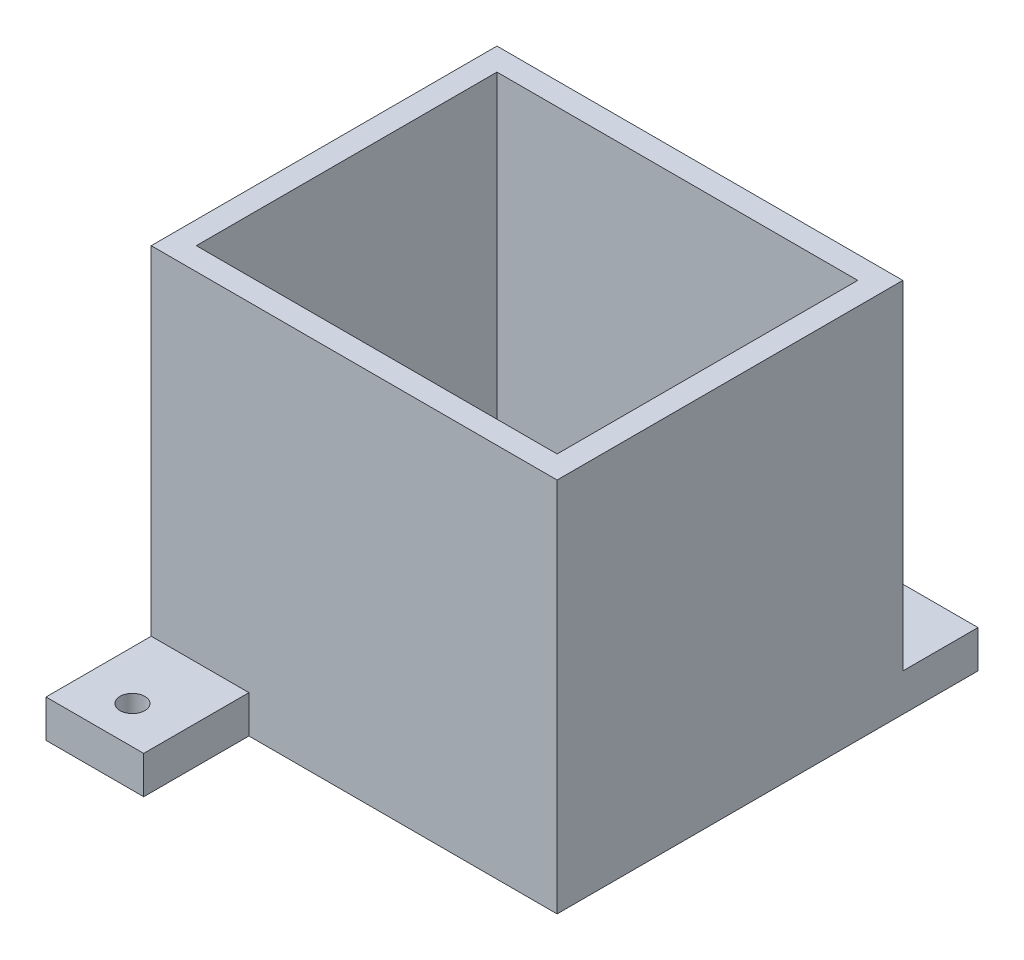
SolidWorks part; units mm, degrees
ref_plane "Front Plane" through (0, 0, 0) normal (0, 0, 1) x (1, 0, 0)
ref_plane "Top Plane" through (0, 0, 0) normal (0, 1, 0) x (1, 0, 0)
ref_plane "Right Plane" through (0, 0, 0) normal (1, 0, 0) x (0, 0, -1)
sketch "Sketch1" plane through (0, 0, 0) normal (0, 1, 0) x (1, 0, 0)
  line L1 (-21.7354, 20.4392) -> (26.2646, 20.4392)
  line L2 (-21.7354, 20.4392) -> (-21.7354, -19.5608)
  line L3 (-21.7354, -19.5608) -> (26.2646, -19.5608)
  line L4 (26.2646, 20.4392) -> (26.2646, -19.5608)
  line L5 (-24.7354, 23.4392) -> (29.2646, 23.4392)
  line L6 (-24.7354, 23.4392) -> (-24.7354, -22.5608)
  line L7 (-24.7354, -22.5608) -> (29.2646, -22.5608)
  line L8 (29.2646, 23.4392) -> (29.2646, -22.5608)
  dimension "D1" = 48
  dimension "D2" = 40
  dimension "D3" = 3
  dimension "D4" = 3
  dimension "D5" = 3
  dimension "D6" = 3
extrude "Boss-Extrude1" add sketch "Sketch1" along normal blind 50 contours L8 L5 L6 L7 L1 L4 L3 L2
sketch "Sketch2" plane through (0, 0, 0) normal (0, 1, 0) x (1, 0, 0)
  line L0 (29.2646, 23.4392) -> (29.2646, -22.5608) construction
  line L1 (-24.7354, 23.4392) -> (29.2646, 23.4392)
  line L2 (-24.7354, 23.4392) -> (-24.7354, 33.4392)
  line L3 (-24.7354, 33.4392) -> (29.2646, 33.4392)
  line L4 (29.2646, 23.4392) -> (29.2646, 33.4392)
  line L6 (-24.7354, -22.5608) -> (-11.7354, -22.5608)
  line L7 (-24.7354, -22.5608) -> (-24.7354, -36.5608)
  line L8 (-24.7354, -36.5608) -> (-11.7354, -36.5608)
  line L9 (-11.7354, -22.5608) -> (-11.7354, -36.5608)
  circle A0 centre (21.7646, 28.4392) radius 1.65
  circle A1 centre (1.7646, 28.4392) radius 1.65
  circle A2 centre (-18.2354, 28.4392) radius 1.65
  circle A3 centre (-18.2354, -31.5608) radius 1.65
  point P11 (29.2646, 28.4392)
  point P21 (0, 0)
  point P22 (0, 0)
  point P23 (0, 0)
  dimension "D2" = 3.3
  dimension "D7" = 3.3
  dimension "D1" = 10
  dimension "D3" = 7.5
  dimension "D5" = 14
  dimension "D6" = 13
  dimension "D8" = 9
  dimension "D4" = 3
extrude "Boss-Extrude2" add sketch "Sketch2" along normal blind 5 contours L1 L4 L3 L2 A2 A1 A0 | L9 L6 L7 L8 A3
